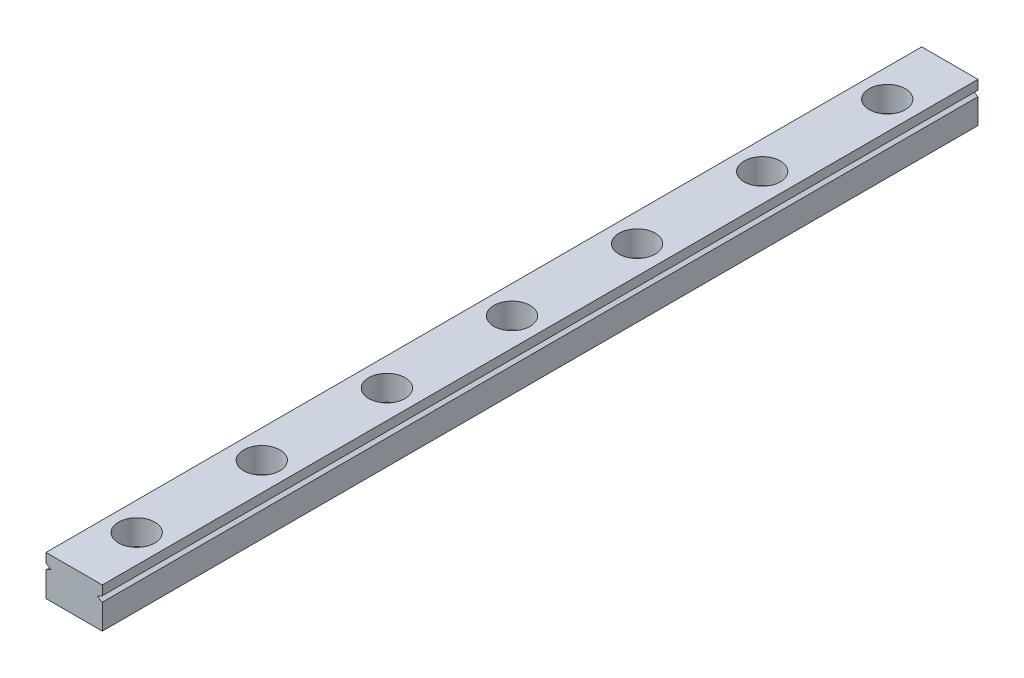
SolidWorks part; units mm, degrees
ref_plane "Front Plane" through (0, 0, 0) normal (0, 0, 1) x (1, 0, 0)
ref_plane "Top Plane" through (0, 0, 0) normal (0, 1, 0) x (1, 0, 0)
ref_plane "Right Plane" through (0, 0, 0) normal (1, 0, 0) x (0, 0, -1)
sketch "Sketch1" plane through (0, 0, 0) normal (0, 0, 1) x (1, 0, 0)
  line L0 (9, 6.4) -> (9, 4.9)
  line L1 (0, 0) -> (9, 0)
  line L2 (0, 0) -> (0, 6.4) construction
  line L3 (0, 6.4) -> (9, 6.4)
  line L4 (9, 0) -> (9, 6.4) construction
  line L5 (9, 4.9) -> (8.2, 4.45)
  line L6 (8.2, 4.45) -> (9, 4)
  line L7 (9, 4) -> (9, 0)
  line L8 (0, 6.4) -> (0, 4.9)
  line L9 (0, 4.9) -> (0.8, 4.45)
  line L10 (0.8, 4.45) -> (0, 4)
  line L11 (0, 4) -> (0, 0)
  line L12 (4.5, 6.4) -> (4.5, 0) construction
  line L13 (9, 4.9) -> (9, 4) construction
  line L14 (9, 4.45) -> (0, 4.45) construction
  point P15 (0, 0)
  point P16 (0, 0)
  dimension "D1" = 9
  dimension "D2" = 6.4
  dimension "D3" = 1.5
  dimension "D4" = 4
  dimension "D5" = 0.8
extrude "Boss-Extrude1" add sketch "Sketch1" along normal blind 140
sketch "Sketch2" plane through (0, 6.4, 0) normal (0, 1, 0) x (1, 0, 0)
  line L0 (4.5, -140) -> (4.5, 0) construction
  line L1 (9, -140) -> (0, -140) construction
  line L2 (9, 0) -> (0, 0) construction
  circle A0 centre (4.5, -130) radius 2.9
  circle A1 centre (4.5, -110) radius 2.9
  circle A2 centre (4.5, -90) radius 2.9
  circle A3 centre (4.5, -70) radius 2.9
  circle A4 centre (4.5, -50) radius 2.9
  circle A5 centre (4.5, -30) radius 2.9
  circle A6 centre (4.5, -10) radius 2.9
  dimension "D1" = 5.8
  dimension "D2" = 10
  dimension "D3" = 7
extrude "Cut-Extrude1" cut sketch "Sketch2" against normal blind 4
sketch "Sketch3" plane through (0, 2.4, 0) normal (0, 1, 0) x (1, 0, 0)
  circle A0 centre (4.5, -130) radius 1.7
  circle A1 centre (4.5, -130) radius 2.9 construction
  circle A2 centre (4.5, -110) radius 1.7
  circle A3 centre (4.5, -90) radius 1.7
  circle A4 centre (4.5, -70) radius 1.7
  circle A5 centre (4.5, -50) radius 1.7
  circle A6 centre (4.5, -30) radius 1.7
  circle A7 centre (4.5, -10) radius 1.7
  dimension "D1" = 3.4
  dimension "D2" = 7
extrude "Cut-Extrude2" cut sketch "Sketch3" against normal through all
